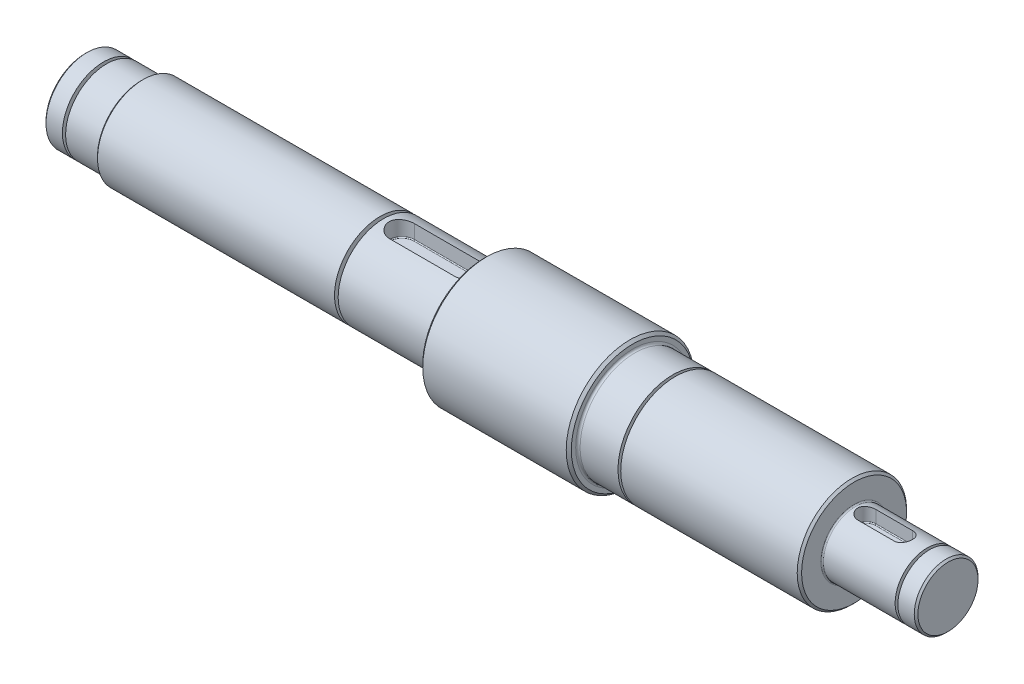
SolidWorks part; units mm, degrees
ref_plane "Front Plane" through (0, 0, 0) normal (0, 0, 1) x (1, 0, 0)
ref_plane "Top Plane" through (0, 0, 0) normal (0, 1, 0) x (1, 0, 0)
ref_plane "Right Plane" through (0, 0, 0) normal (1, 0, 0) x (0, 0, -1)
sketch "Sketch1" plane through (0, 0, 0) normal (0, 0, 1) x (1, 0, 0)
  line L0 (-215, 0) -> (215, 0) construction
  line L1 (-215, 0) -> (-215, 22.5)
  line L2 (-215, 22.5) -> (-196, 22.5)
  line L3 (-196, 22.5) -> (-196, 25)
  line L4 (-196, 25) -> (-65, 25)
  line L5 (-8, 25) -> (-8, 35)
  line L6 (-8, 35) -> (73.5, 35)
  line L7 (73.5, 35) -> (73.5, 30)
  line L9 (195, 30) -> (195, 17.5)
  line L10 (195, 17.5) -> (235, 17.5)
  line L12 (215, 0) -> (-215, 0)
  line L13 (-63, 25) -> (-63, 0) construction
  line L14 (-63, 25) -> (-8, 25)
  line L15 (236.5, 17.5) -> (246.5, 17.5)
  line L16 (246.5, 17.5) -> (246.5, 0)
  line L17 (246.5, 0) -> (215, 0)
  line L18 (95.5, 30) -> (95.5, 26.5)
  line L19 (95.5, 30) -> (95.5, 0) construction
  line L20 (97, 30) -> (195, 30)
  line L21 (235, 17.5) -> (235, 13.6)
  line L22 (235, 13.6) -> (236.5, 13.6)
  line L23 (236.5, 13.6) -> (236.5, 17.5)
  line L24 (95.5, 26.5) -> (97, 26.5)
  line L25 (97, 26.5) -> (97, 30)
  line L26 (-63, 25) -> (-63, 19.9)
  line L27 (-63, 19.9) -> (-65, 19.9)
  line L28 (-65, 19.9) -> (-65, 25)
  line L30 (73.5, 30) -> (95.5, 30)
  point P4 (0, 0)
  dimension "D2" = 22.5
  dimension "D6" = 70
  dimension "D12" = 5.1
  dimension "D14" = 3.9
  dimension "D15" = 1.5
  dimension "D18" = 461.5
  dimension "D19" = 3.5
  dimension "D1" = 430
  dimension "D3" = 19
  dimension "D4" = 25
  dimension "D5" = 188
  dimension "D7" = 22
  dimension "D8" = 121.5
  dimension "D9" = 81.5
  dimension "D10" = 40
  dimension "D11" = 55
  dimension "D13" = 2
  dimension "D16" = 1.5
  dimension "D17" = 17.5
  dimension "D20" = 10
  dimension "D21" = 1.5
  dimension "D22" = 30
  dimension "D23" = 30
revolve "Revolve1" add sketch "Sketch1" angle 360 about L0
fillet "Fillet1" [suppressed] radius 10
fillet "Fillet2" [suppressed] radius 3
fillet "Fillet3" [suppressed] radius 10
fillet "Fillet4" [suppressed] radius 3
sketch "Sketch2" plane through (-215, 0, 0) normal (-1, 0, 0) x (0, 0, 1)
  circle A1 centre (0, 0) radius 22.5
  circle A2 centre (0, 0) radius 22.5
  dimension "D1" = 0
extrude "Boss-Extrude1" add sketch "Sketch2" along normal blind 11.75 separate body
sketch "Sketch3" plane through (0, 0, 0) normal (0, 0, 1) x (1, 0, 0)
  line L0 (-226.75, 0) -> (0, 0) construction
  line L1 (-226.75, 22.5) -> (-226.75, -22.5) construction
  line L2 (-215, 22.5) -> (-215, 17.8)
  line L3 (-215, 22.5) -> (-215, -22.5) construction
  line L4 (-215, 17.8) -> (-216.75, 17.8)
  line L5 (-216.75, 17.8) -> (-216.75, 22.5)
  line L6 (-216.75, 22.5) -> (-215, 22.5)
  dimension "D1" = 4.7
  dimension "D2" = 1.75
revolve "Cut-Revolve1" cut sketch "Sketch3" angle 360 about L0
ref_plane "Plane1" through (202, 0, 0) normal (1, 0, 0) x (0, 0, -1)
sketch "Sketch4" plane through (202, 0, 0) normal (1, 0, 0) x (0, 0, -1)
  line L0 (0, 0) -> (0, 17.5) construction
  line L1 (0, 17.5) -> (0, 9.5) construction
  line L2 (-5, 9.5) -> (5, 9.5)
  line L3 (5, 9.5) -> (5, 16.7705)
  line L4 (-5, 9.5) -> (-5, 16.7705)
  circle A0 centre (0, 0) radius 17.5 construction
  arc A1 (5, 16.7705) -> (-5, 16.7705) centre (0, 0) ccw
  point P8 (0, 9.5)
  dimension "D1" = 10
  dimension "D2" = 8
extrude "Cut-Extrude1" cut sketch "Sketch4" along normal blind 20
ref_plane "Plane2" through (-17, 0, 0) normal (-1, 0, 0) x (0, 0, 1)
sketch "Sketch5" plane through (-17, 0, 0) normal (-1, 0, 0) x (0, 0, 1)
  line L0 (0, 25) -> (0, 16) construction
  line L1 (-7, 16) -> (7, 16)
  line L2 (7, 16) -> (7, 24)
  line L3 (-7, 16) -> (-7, 24)
  circle A0 centre (0, 0) radius 25 construction
  arc A1 (7, 24) -> (-7, 24) centre (0, 0) ccw
  point P9 (0, 16)
  dimension "D1" = 9
  dimension "D2" = 14
extrude "Cut-Extrude2" cut sketch "Sketch5" along normal blind 36
fillet "Fillet5" radius 1 1 edges at (-8, 0, 25)
chamfer "Chamfer1" distance 1.4 angle 45 1 edges at (-8, 0, 35)
chamfer "Chamfer2" distance 1.4 angle 45 1 edges at (73.5, 0, 35)
fillet "Fillet6" radius 1.2 1 edges at (73.5, 0, 30)
fillet "Fillet7" radius 0.9 1 edges at (-196, 0, 22.5)
chamfer "Chamfer3" distance 1 angle 45 1 edges at (-196, 0, 25)
chamfer "Chamfer4" distance 1.2 angle 45 1 edges at (195, 0, 30)
fillet "Fillet8" radius 0.7 1 edges at (195, 0, 17.5)
ref_plane "Plane3" through (0, 25, 0) normal (0, 1, 0) x (1, 0, 0)
sketch "Sketch6" plane through (0, 25, 0) normal (0, 1, 0) x (1, 0, 0)
  line L0 (-53, -7) -> (-53, 7) construction
  line L1 (-17, 7) -> (-17, -7) construction
  line L2 (-53, 7) -> (-53, -7)
  line L3 (-17, 7) -> (-17, -7)
  arc A0 (-53, 7) -> (-53, -7) centre (-53, 0) ccw
  arc A1 (-17, -7) -> (-17, 7) centre (-17, 0) ccw
  dimension "D1" = 14
extrude "Cut-Extrude3" cut sketch "Sketch6" against normal up to surface (9 mm away) up to face at (-35, 16, 0)
ref_plane "Plane4" through (0, 17.5, 0) normal (0, 1, 0) x (1, 0, 0)
sketch "Sketch7" plane through (0, 17.5, 0) normal (0, 1, 0) x (1, 0, 0)
  line L0 (202, -5) -> (202, 5) construction
  line L1 (222, -5) -> (222, 5) construction
  line L2 (202, 5) -> (202, -5)
  line L3 (222, 5) -> (222, -5)
  arc A0 (202, 5) -> (202, -5) centre (202, 0) ccw
  arc A1 (222, -5) -> (222, 5) centre (222, 0) ccw
extrude "Cut-Extrude4" cut sketch "Sketch7" against normal up to surface (8 mm away) up to face at (212, 9.5, 0)
fillet "Fillet9" radius 0.4 2 edges at (-65, 0, 19.9) (-63, 0, 19.9)
fillet "Fillet10" radius 0.4 1 edges at (-216.75, 0, 17.8)
fillet "Fillet11" radius 0.4 1 edges at (97, 0, 26.5)
fillet "Fillet12" radius 0.4 1 edges at (95.5, 0, 26.5)
fillet "Fillet13" radius 0.4 2 edges at (236.5, 0, 13.6) (235, 0, 13.6)
sketch "Sketch8" plane through (0, 0, 0) normal (0, 0, 1) x (1, 0, 0)
  line L1 (-226.75, 0) -> (-216.75, 0) construction
  line L2 (-226.75, 22.5) -> (-226.75, -22.5) construction
  line L3 (-215, 22.5) -> (-215, -22.5) construction
  line L4 (-215.4, 17.8) -> (-215, 17.8)
  line L5 (-215, 17.8) -> (-215, 18.2)
  line L6 (-216.75, -18.2) -> (-216.75, 18.2) construction
  arc A0 (-215.4, 17.8) -> (-215, 18.2) centre (-215.4, 18.2) ccw
  dimension "D1" = 0.4
revolve "Revolve2" add sketch "Sketch8" angle 360 about L1
fillet "Fillet14" radius 0.5 8 edges at (227, 9.5, 0) (212, 9.5, 5) (197, 9.5, 0) (-60, 16, 0) (-35, 16, 7) (-10, 16, 0) (212, 9.5, -5) (-35, 16, -7)
chamfer "Chamfer5" distance 1 angle 45 1 edges at (246.5, 0, 17.5)
chamfer "Chamfer6" distance 1 angle 45 1 edges at (-226.75, 0, 22.5)
